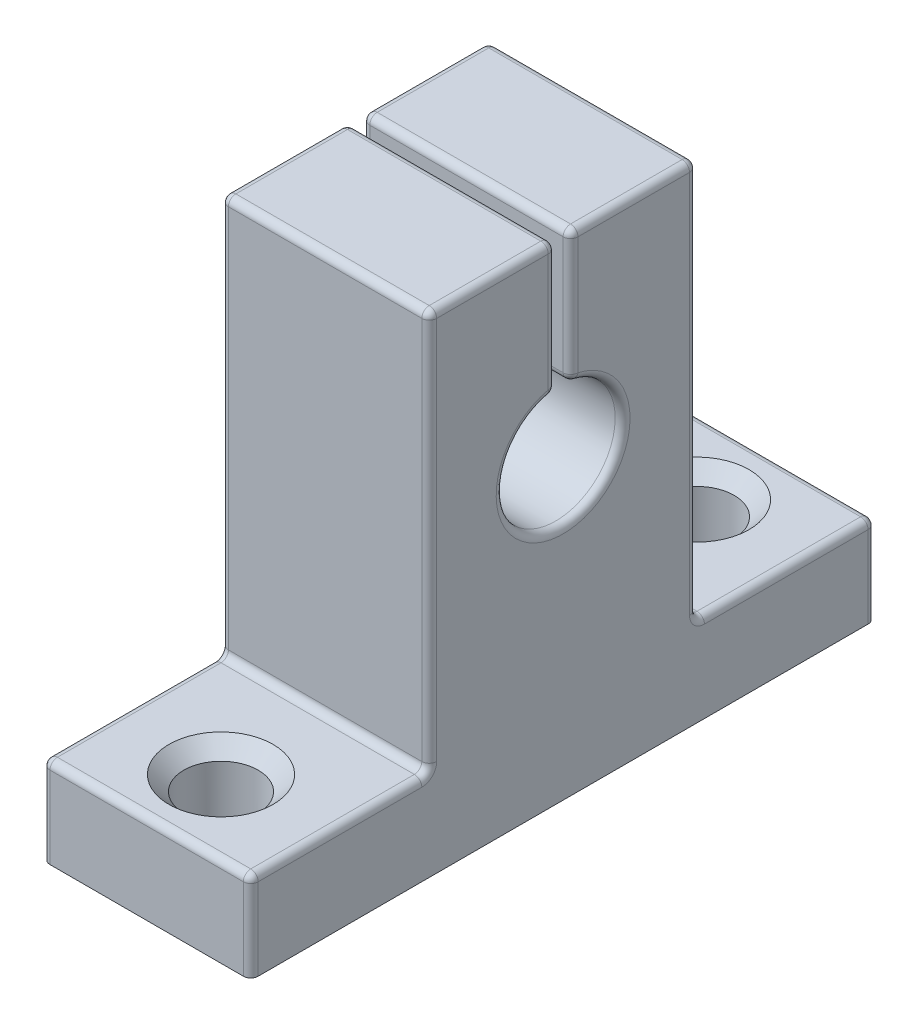
SolidWorks part; units mm, degrees
ref_plane "Front Plane" through (0, 0, 0) normal (0, 0, 1) x (1, 0, 0)
ref_plane "Top Plane" through (0, 0, 0) normal (0, 1, 0) x (1, 0, 0)
ref_plane "Right Plane" through (0, 0, 0) normal (1, 0, 0) x (0, 0, -1)
sketch "Sketch1" plane through (0, 0, 0) normal (1, 0, 0) x (0, 0, -1)
  line L0 (-21, 0) -> (21, 0)
  line L1 (21, 0) -> (21, 6)
  line L2 (21, 6) -> (9, 6)
  line L3 (9, 6) -> (9, 32.8)
  line L4 (9, 32.8) -> (0.5, 32.8)
  line L6 (-0.5, 32.8) -> (-9, 32.8)
  line L7 (-9, 32.8) -> (-9, 6)
  line L8 (-9, 6) -> (-21, 6)
  line L9 (-21, 6) -> (-21, 0)
  line L10 (-0.5, 32.8) -> (-0.5, 23.9686)
  line L11 (0.5, 32.8) -> (0.5, 23.9686)
  arc A0 (-0.5, 23.9686) -> (0.5, 23.9686) centre (0, 20) ccw
  dimension "D3" = 4
  dimension "D1" = 42
  dimension "D2" = 18
  dimension "D4" = 1
  dimension "D5" = 20
  dimension "D6" = 32.8
  dimension "D7" = 6
extrude "Boss-Extrude1" add sketch "Sketch1" along normal mid plane 14
sketch "Sketch3" plane through (0, 6, 0) normal (0, 1, 0) x (1, 0, 0)
  line L0 (0, 16) -> (0, 0) construction
  line L1 (0, 0) -> (0, -16) construction
  circle A0 centre (0, 16) radius 2.5
  circle A1 centre (0, -16) radius 2.5
  dimension "D2" = 5
  dimension "D1" = 32
extrude "Cut-Extrude1" cut sketch "Sketch3" against normal up to surface (6 mm away) up to face at (0, 0, 0)
fillet "Fillet2" radius 0.5 32 edges at (7, 6, -15) (-7, 6, -15) (7, 6, 15) (-7, 6, 15) (7, 28.3843, 0.5) (-7, 28.3843, 0.5) (7, 28.3843, -0.5) (-7, 28.3843, -0.5) (0, 23.9686, -0.5) (7, 16, 0) (0, 23.9686, 0.5) (-7, 16, 0) (0, 6, -9) (7, 19.4, -9) (-7, 19.4, -9) (7, 19.4, 9) (0, 6, 9) (-7, 19.4, 9) (0, 32.8, -9) (7, 32.8, -4.75) (0, 32.8, -0.5) (-7, 32.8, -4.75) (0, 32.8, 0.5) (7, 32.8, 4.75) (0, 32.8, 9) (-7, 32.8, 4.75) (7, 3, 21) (-7, 3, 21) (-7, 3, -21) (7, 3, -21) (0, 6, -21) (0, 6, 21)
chamfer "Chamfer1" distance 1 angle 45 2 edges at (0, 6, -13.5) (0, 6, 18.5)
